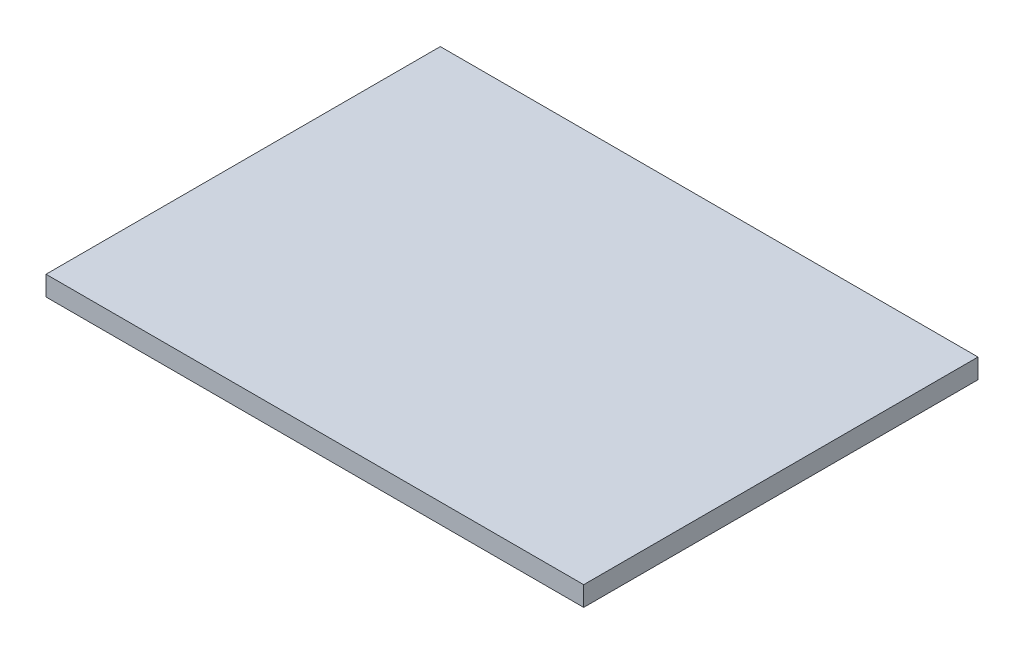
SolidWorks part; units mm, degrees
ref_plane "前视基准面" through (0, 0, 0) normal (0, 0, 1) x (1, 0, 0)
ref_plane "上视基准面" through (0, 0, 0) normal (0, 1, 0) x (1, 0, 0)
ref_plane "右视基准面" through (0, 0, 0) normal (1, 0, 0) x (0, 0, -1)
other "Configuration Table"
sketch "草图1" plane through (0, 0, 0) normal (0, 1, 0) x (1, 0, 0)
  line L1 (0, 0) -> (30, 0)
  line L2 (0, 0) -> (0, 22)
  line L3 (0, 22) -> (30, 22)
  line L4 (30, 0) -> (30, 22)
  line L5 (0, 0) -> (30, 22) construction
  line L6 (0, 22) -> (30, 0) construction
  point P4 (15, 11)
  dimension "D1" = 30
  dimension "D2" = 22
extrude "凸台-拉伸1" add sketch "草图1" along normal blind 1.1
